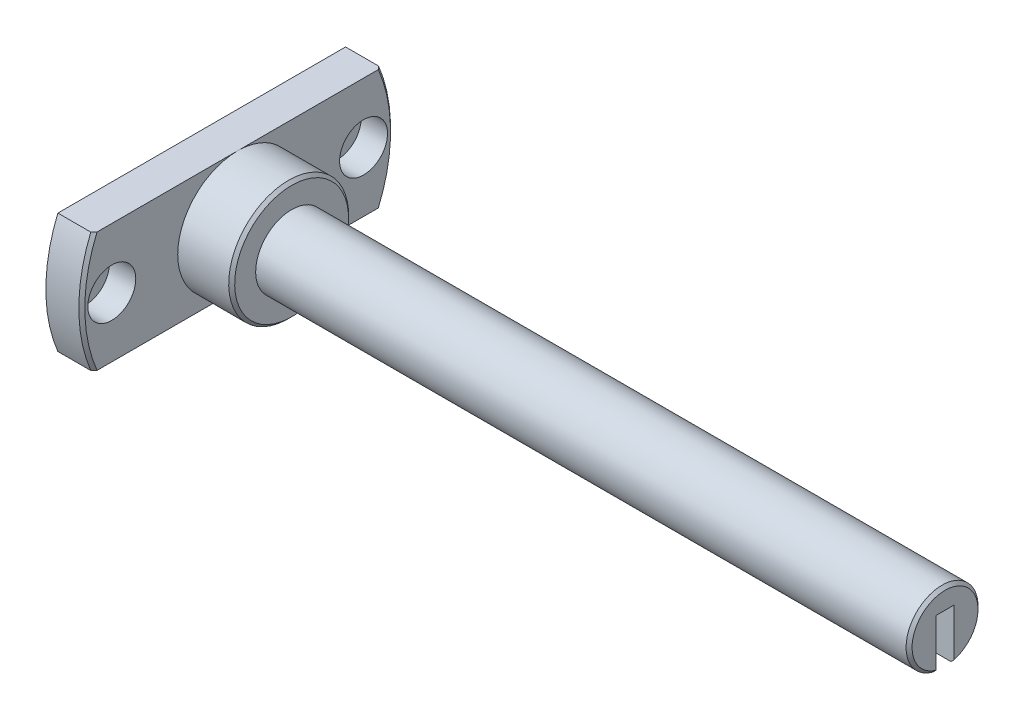
SolidWorks part; units mm, degrees
material "3.1325 (EN-AW 2017A)"
ref_plane "Plan de face" through (0, 0, 0) normal (0, 0, 1) x (1, 0, 0)
ref_plane "Plan de dessus" through (0, 0, 0) normal (0, 1, 0) x (1, 0, 0)
ref_plane "Plan de droite" through (0, 0, 0) normal (1, 0, 0) x (0, 0, -1)
sketch "Esquisse1" plane through (0, 0, 0) normal (0, 0, 1) x (1, 0, 0)
  line L0 (15, 6) -> (124, 6)
  line L1 (124, 6) -> (124, 0)
  line L2 (124, 0) -> (0, 0)
  line L3 (0, 0) -> (0, 26)
  line L4 (6, 10) -> (15, 10)
  line L5 (15, 10) -> (15, 6)
  line L7 (0, 26) -> (6, 26)
  line L8 (6, 26) -> (6, 10)
  dimension "D1" = 124
  dimension "D3" = 6
  dimension "D4" = 15
  dimension "D5" = 6
  dimension "D6" = 10
  dimension "D7" = 20
revolve "Révolution1" add sketch "Esquisse1" angle 360 about L2
chamfer "Chanfrein1" distance 0.5 angle 45 2 edges at (15, 10, 0) (6, 26, 0)
hole_wizard "Chambrage pour vis à tête hexagonale M41" positions "Esquisse4" profile "Esquisse2" counterbore size "M4" standard "ISO" end condition through all
sketch "Esquisse4" plane through (6, 0, 0) normal (1, 0, 0) x (0, 0, -1)
  line L0 (21, 0) -> (0, 0) construction
  line L1 (0, 0) -> (-21, 0) construction
  line L2 (0, 5.6863) -> (0, -6.4906) construction
  point P0 (-21, 0)
  point P2 (21, 0)
  dimension "D1" = 42
sketch "Esquisse2" plane through (6, 0, 21) normal (0, 1, 0) x (0, 0, -1)
  line L0 (0, 0) -> (0, 6)
  line L1 (0, 6) -> (2.25, 6)
  line L3 (2.25, 6) -> (2.25, 4.4)
  line L4 (2.25, 4.4) -> (4, 4.4)
  line L5 (4, 4.4) -> (4, 0)
  line L7 (4, 0) -> (0, 0)
  line L11 (0, -6.35) -> (0, 107.95) construction
  dimension "Diamètre du perçage jusqu'au prochain" = 4.5
  dimension "Profondeur du perçage jusqu'au prochain" = 6
  dimension "Diamètre du chambrage" = 8
  dimension "Profondeur du chambrage" = 4.4
sketch "Esquisse9" plane through (6, 0, 0) normal (1, 0, 0) x (0, 0, -1)
  point P0 (-21, 0)
  point P1 (21, 0)
sketch "Esquisse10" plane through (124, 0, 0) normal (1, 0, 0) x (0, 0, -1)
  line L0 (0, 15.042) -> (0, -18.3339) construction
sketch "Esquisse11" plane through (0, 0, 0) normal (-1, 0, 0) x (0, 0, 1)
  line L0 (24, -10) -> (-24, -10)
  line L2 (-33.9621, 0) -> (34.1744, 0) construction
  line L3 (24, 10) -> (-24, 10)
  circle A0 centre (0, 0) radius 26 construction
  arc A1 (-24, -10) -> (24, -10) centre (0, 0) ccw
  arc A2 (-24, 10) -> (24, 10) centre (0, 0) cw
  dimension "D1" = 20
extrude "Enlèv. mat.-Extru.2" cut sketch "Esquisse11" against normal through all
chamfer "Chanfrein3" distance 0.5 angle 45 1 edges at (124, 6, 0)
sketch "Esquisse12" plane through (124, 0, 0) normal (1, 0, 0) x (0, 0, -1)
  line L1 (-1.5, -9.0025) -> (1.5, -9.0025)
  line L2 (-1.5, -9.0025) -> (-1.5, 2.6186)
  line L3 (-1.5, 2.6186) -> (1.5, 2.6186)
  line L4 (1.5, -9.0025) -> (1.5, 2.6186)
  line L5 (-1.5, -9.0025) -> (1.5, 2.6186) construction
  line L6 (-1.5, 2.6186) -> (1.5, -9.0025) construction
  point P0 (0, 0)
  dimension "D1" = 3
extrude "Enlèv. mat.-Extru.3" cut sketch "Esquisse12" against normal blind 3
hole_wizard "Dégagement M21" positions "Esquisse14" profile "Esquisse15" hole size "M2" standard "JIS"
sketch "Esquisse14" plane through (121, 0, 0) normal (1, 0, 0) x (0, 0, -1)
  point P1 (0, 0)
  point P4 (0, -3.7249)
sketch "Esquisse15" plane through (121, 0, 0) normal (0, 1, 0) x (0, 0, -1)
  line L0 (0, 0) -> (0, 5.6928)
  line L1 (0, 5.6928) -> (1.2, 5)
  line L2 (1.2, 5) -> (1.2, 0)
  line L5 (1.2, 0) -> (0, 0)
  line L10 (0, 5.6928) -> (-1.2, 5) construction
  line L11 (0, -6.35) -> (0, 107.95) construction
  dimension "Diamètre du perçage" = 2.4
  dimension "Profondeur du perçage" = 5
  dimension "Angle de pointe" = 120
